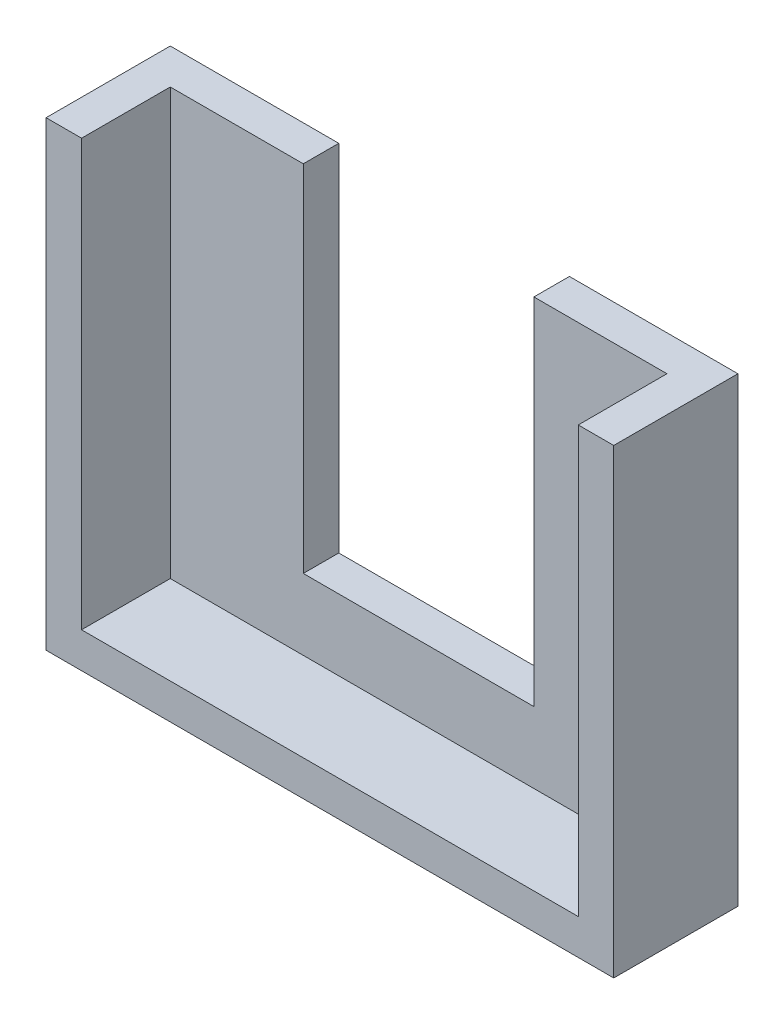
SolidWorks part; units mm, degrees
ref_plane "前视基准面" through (0, 0, 0) normal (0, 0, 1) x (1, 0, 0)
ref_plane "上视基准面" through (0, 0, 0) normal (0, 1, 0) x (1, 0, 0)
ref_plane "右视基准面" through (0, 0, 0) normal (1, 0, 0) x (0, 0, -1)
sketch "草图1" plane through (0, 0, 0) normal (0, 0, 1) x (1, 0, 0)
  line L1 (-80, -65) -> (80, -65)
  line L2 (-80, -65) -> (-80, 65)
  line L3 (-80, 65) -> (80, 65)
  line L4 (80, -65) -> (80, 65)
  line L5 (-80, -65) -> (80, 65) construction
  line L6 (-80, 65) -> (80, -65) construction
  point P0 (0, 0)
  dimension "D1" = 160
  dimension "D2" = 130
extrude "凸台-拉伸1" add sketch "草图1" along normal blind 10
sketch "草图2" plane through (0, 0, 10) normal (0, 0, 1) x (1, 0, 0)
  line L0 (-32.5, 35) -> (-32.5, 65)
  line L1 (-32.5, -35) -> (32.5, -35)
  line L2 (-32.5, -35) -> (-32.5, 35)
  line L4 (32.5, -35) -> (32.5, 35)
  line L5 (-32.5, -35) -> (32.5, 35) construction
  line L6 (-32.5, 35) -> (32.5, -35) construction
  line L7 (80, 65) -> (-80, 65) construction
  line L8 (-32.5, 65) -> (32.5, 65)
  line L9 (32.5, 65) -> (32.5, 35)
  point P0 (0, 0)
  dimension "D1" = 65
  dimension "D2" = 70
extrude "切除-拉伸1" cut sketch "草图2" against normal blind 10
sketch "草图3" plane through (0, 0, 10) normal (0, 0, 1) x (1, 0, 0)
  line L0 (-70, 65) -> (-70, -55)
  line L1 (-70, -55) -> (70, -55)
  line L2 (70, -55) -> (70, 65)
  line L3 (80, 65) -> (32.5, 65) construction
  line L4 (70, 65) -> (80, 65)
  line L5 (80, 65) -> (80, -65)
  line L6 (80, -65) -> (-80, -65)
  line L7 (-80, -65) -> (-80, 65)
  line L8 (-80, 65) -> (-70, 65)
  line L9 (-32.5, 65) -> (-80, 65) construction
  point P14 (-75.086, 63.8858)
  dimension "D1" = 10
  dimension "D2" = 10
  dimension "D3" = 10
extrude "凸台-拉伸2" add sketch "草图3" along normal blind 25
